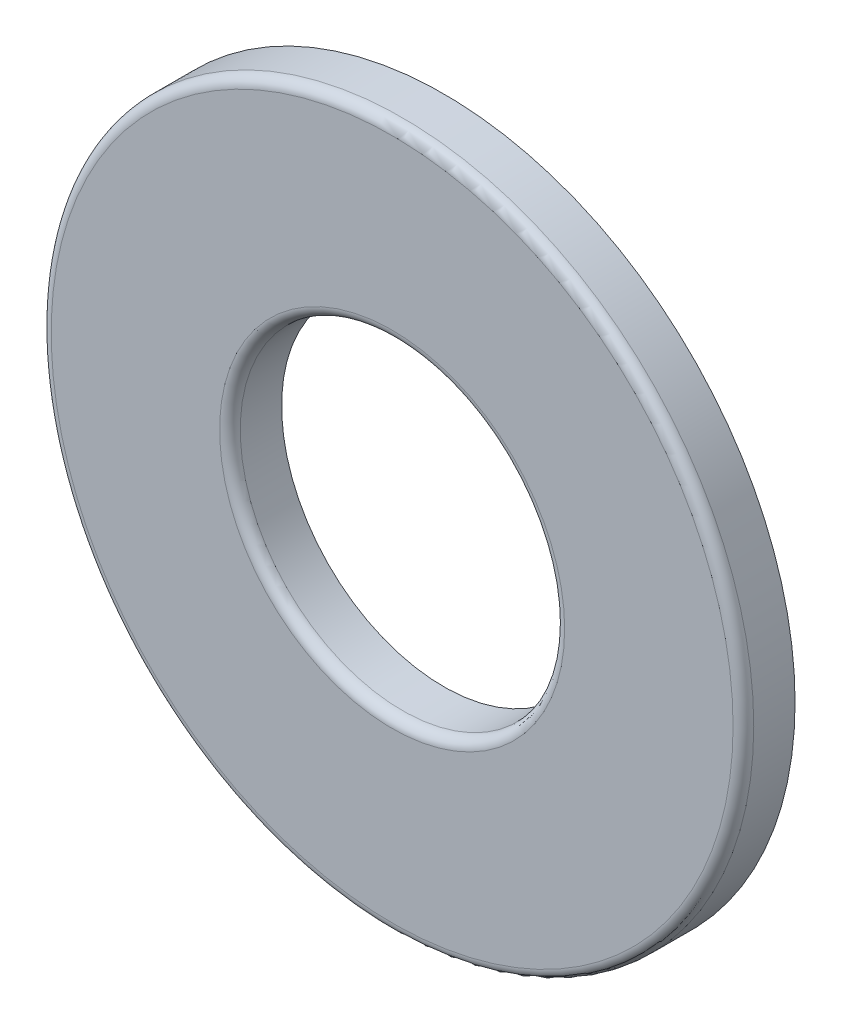
SolidWorks part; units mm, degrees
material "Chrome Stainless Steel"
ref_plane "Front Plane" through (0, 0, 0) normal (0, 0, 1) x (1, 0, 0)
ref_plane "Top Plane" through (0, 0, 0) normal (0, 1, 0) x (1, 0, 0)
ref_plane "Right Plane" through (0, 0, 0) normal (1, 0, 0) x (0, 0, -1)
sketch "Sketch1" plane through (0, 0, 0) normal (0, 0, 1) x (1, 0, 0)
  circle A0 centre (0, 0) radius 1.57
  circle A1 centre (0, 0) radius 3.4
  dimension "D1" = 6.8
  dimension "D2" = 3.14
extrude "Boss-Extrude1" add sketch "Sketch1" along normal blind 0.5
fillet "Fillet1" radius 0.1 2 edges at (1.57, 0, 0.5) (3.4, 0, 0.5)
